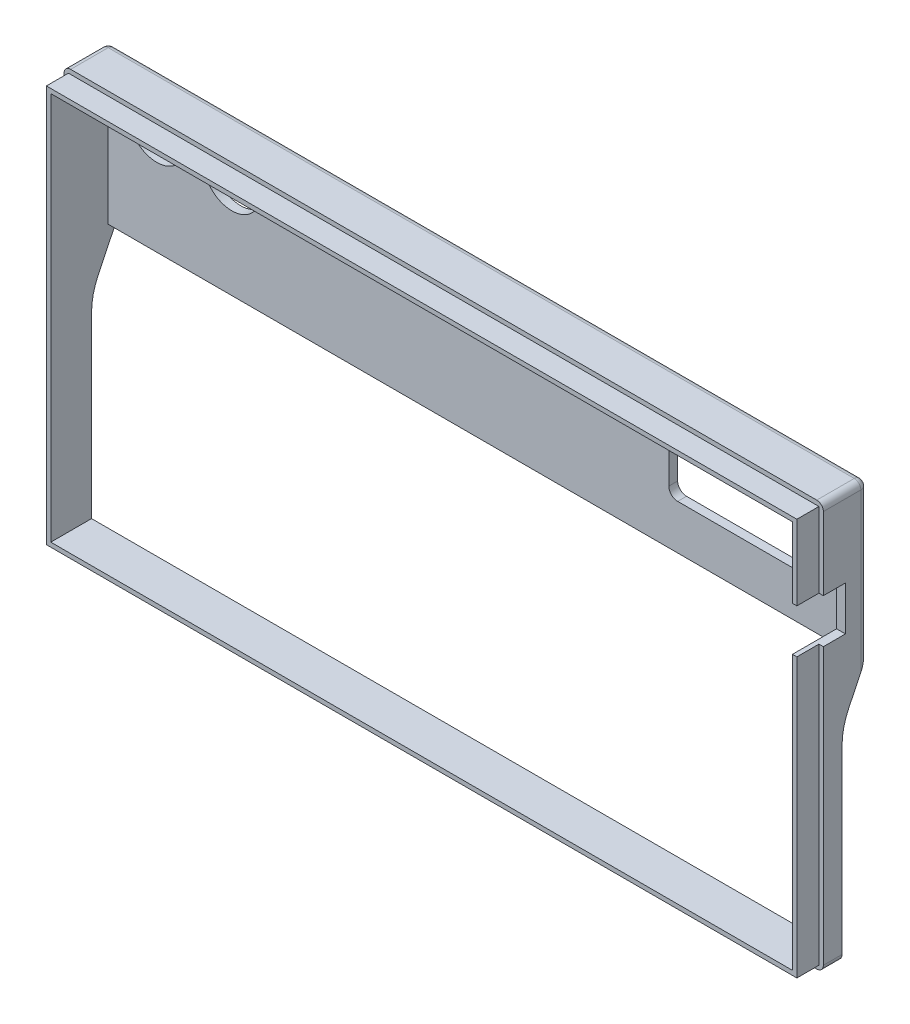
SolidWorks part; units mm, degrees
ref_plane "前视基准面" through (0, 0, 0) normal (0, 0, 1) x (1, 0, 0)
ref_plane "上视基准面" through (0, 0, 0) normal (0, 1, 0) x (1, 0, 0)
ref_plane "右视基准面" through (0, 0, 0) normal (1, 0, 0) x (0, 0, -1)
sketch "草图1" plane through (0, 0, 0) normal (0, 0, 1) x (1, 0, 0)
  line L1 (-84.74, 35.0923) -> (87.26, 35.0923)
  line L2 (-84.74, 35.0923) -> (-84.74, -56.9077)
  line L3 (-84.74, -56.9077) -> (87.26, -56.9077)
  line L4 (87.26, 35.0923) -> (87.26, -56.9077)
  dimension "D1" = 172
  dimension "D2" = 92
extrude "凸台-拉伸1" add sketch "草图1" along normal blind 2
sketch "草图2" plane through (0, 0, 0) normal (0, 0, -1) x (-1, 0, 0)
  line L0 (-87.26, 35.0923) -> (84.74, 35.0923) construction
  line L1 (-76.26, 33.0923) -> (-44.26, 33.0923)
  line L2 (-76.26, 33.0923) -> (-76.26, 11.0923)
  line L3 (-76.26, 11.0923) -> (-44.26, 11.0923)
  line L4 (-44.26, 33.0923) -> (-44.26, 11.0923)
  line L5 (-87.26, -56.9077) -> (-87.26, 35.0923) construction
  dimension "D1" = 2
  dimension "D2" = 11
  dimension "D3" = 32
  dimension "D4" = 22
extrude "切除-拉伸1" cut sketch "草图2" against normal blind 2
sketch "草图3" plane through (0, 0, 0) normal (0, 0, -1) x (-1, 0, 0)
  line L1 (-87.26, 35.0923) -> (84.74, 35.0923) construction
  line L2 (84.74, 35.0923) -> (84.74, -56.9077) construction
  circle A0 centre (54.74, 24.0923) radius 6.5
  circle A1 centre (71.74, 25.0923) radius 6.5
  dimension "D3" = 13
  dimension "D6" = 13
  dimension "D1" = 10
  dimension "D2" = 13
  dimension "D4" = 11
  dimension "D5" = 17
extrude "切除-拉伸2" cut sketch "草图3" against normal blind 2
sketch "草图4" plane through (0, 0, 2) normal (0, 0, 1) x (1, 0, 0)
  line L0 (87.26, 35.0923) -> (-84.74, 35.0923) construction
  line L1 (-82.74, 33.0923) -> (85.26, 33.0923)
  line L2 (-82.74, 33.0923) -> (-82.74, -54.9077)
  line L3 (-82.74, -54.9077) -> (85.26, -54.9077)
  line L4 (85.26, 33.0923) -> (85.26, -54.9077)
  line L5 (-84.74, 35.0923) -> (-84.74, -56.9077) construction
  line L6 (-84.74, -56.9077) -> (87.26, -56.9077) construction
  line L7 (87.26, -56.9077) -> (87.26, 35.0923) construction
  line M10 (44.26, 33.0923) -> (76.26, 33.0923)
  line M11 (-84.74, 35.0923) -> (-84.74, -56.9077)
  line M12 (-84.74, -56.9077) -> (87.26, -56.9077)
  line M13 (87.26, -56.9077) -> (87.26, 35.0923)
  line M14 (87.26, 35.0923) -> (-84.74, 35.0923)
  dimension "D1" = 2
  dimension "D2" = 2
  dimension "D3" = 2
  dimension "D4" = 2
extrude "凸台-拉伸3" add sketch "草图4" along normal blind 13 contours L1 L4 L3 L2 M14 M11 M12 M13 M10
sketch "草图5" plane through (0, 0, 0) normal (0, 0, -1) x (-1, 0, 0)
  line L0 (-87.26, 35.0923) -> (84.74, 35.0923) construction
  line L1 (-85.26, 0.9623) -> (82.74, 0.9623)
  line L2 (-85.26, 0.9623) -> (-85.26, -54.9077)
  line L3 (-85.26, -54.9077) -> (82.74, -54.9077)
  line L4 (82.74, 0.9623) -> (82.74, -54.9077)
  line L5 (-87.26, -56.9077) -> (-87.26, 35.0923) construction
  line L6 (84.74, -56.9077) -> (-87.26, -56.9077) construction
  line L7 (84.74, 35.0923) -> (84.74, -56.9077) construction
  dimension "D1" = 34.13
  dimension "D2" = 2
  dimension "D3" = 2
  dimension "D4" = 2
extrude "切除-拉伸3" cut sketch "草图5" against normal blind 18
sketch "草图6" plane through (87.26, 0, 0) normal (1, 0, 0) x (0, 0, -1)
  line L0 (0, 0.9623) -> (-5.7624, -10.9918)
  line L1 (0, -56.9077) -> (0, 35.0923) construction
  line L2 (-5.7624, -10.9918) -> (-5.7624, -56.9077)
  line L3 (-15, -56.9077) -> (0, -56.9077) construction
  line L4 (-15, 35.0923) -> (0, 35.0923) construction
  dimension "D1" = 34.13
extrude "切除-拉伸4" cut sketch "草图6" against normal blind 172 and the other way through all
fillet "圆角1" radius 15 2 edges at (-83.74, -10.9918, 5.7624) (86.26, -10.9918, 5.7624)
sketch "草图7" plane through (87.26, 0, 0) normal (1, 0, 0) x (0, 0, -1)
  line L0 (-15, -56.9077) -> (-15, 35.0923) construction
  line L1 (-15, 17.0923) -> (-5, 17.0923)
  line L2 (-15, 17.0923) -> (-15, 7.0923)
  line L3 (-15, 7.0923) -> (-5, 7.0923)
  line L4 (-5, 17.0923) -> (-5, 7.0923)
  line L5 (-15, 35.0923) -> (0, 35.0923) construction
  point P6 (-10, 17.0923)
  dimension "D1" = 18
  dimension "D2" = 10
  dimension "D3" = 10
extrude "切除-拉伸5" cut sketch "草图7" against normal blind 2
sketch "草图8" plane through (0, 0, 15) normal (0, 0, 1) x (1, 0, 0)
  line L0 (87.26, 35.0923) -> (-84.74, 35.0923) construction
  line L1 (-83.74, 34.0923) -> (86.26, 34.0923)
  line L2 (-83.74, 34.0923) -> (-83.74, -55.9077)
  line L3 (-83.74, -55.9077) -> (86.26, -55.9077)
  line L4 (86.26, 34.0923) -> (86.26, -55.9077)
  line L5 (87.26, -56.9077) -> (87.26, 7.0923) construction
  line L6 (-84.74, -56.9077) -> (87.26, -56.9077) construction
  line L7 (-84.74, 35.0923) -> (-84.74, -56.9077) construction
  line M5 (85.26, 17.0923) -> (87.26, 17.0923)
  line M6 (87.26, 17.0923) -> (87.26, 35.0923)
  line M7 (87.26, 35.0923) -> (-84.74, 35.0923)
  line M8 (-84.74, 35.0923) -> (-84.74, -56.9077)
  line M9 (-84.74, -56.9077) -> (87.26, -56.9077)
  line M10 (87.26, -56.9077) -> (87.26, 7.0923)
  line M11 (87.26, 7.0923) -> (85.26, 7.0923)
  dimension "D1" = 1
  dimension "D2" = 1
  dimension "D3" = 1
  dimension "D4" = 1
extrude "切除-拉伸6" cut sketch "草图8" against normal blind 5 contours L1 L4 L3 L2 M5 M6 M7 M8 M9 M10 M11
fillet "圆角2" radius 2 4 edges at (44.26, 11.0923, 1) (76.26, 11.0923, 1) (44.26, 33.0923, 1) (76.26, 33.0923, 1)
fillet "圆角3" radius 1.5 7 edges at (-84.74, 18.0273, 0) (87.26, 18.0273, 0) (1.26, 35.0923, 0) (87.26, -56.9077, 7.8812) (-84.74, -56.9077, 7.8812) (-84.74, 35.0923, 5) (87.26, 35.0923, 5)
